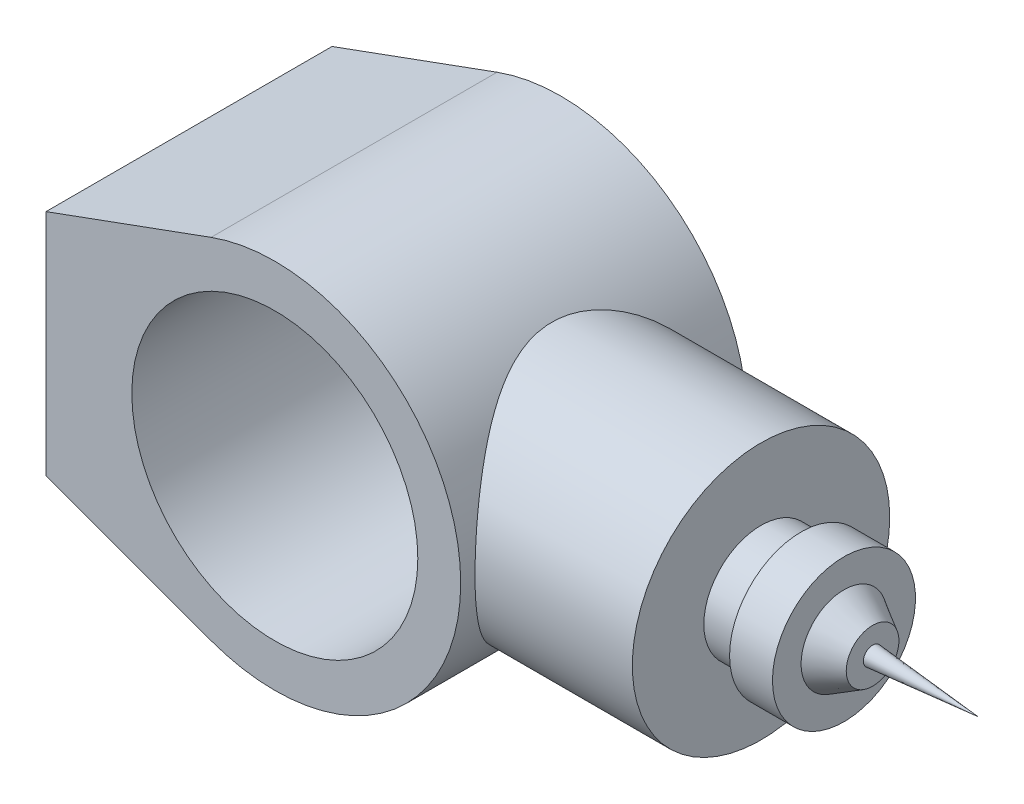
SolidWorks part; units mm, degrees
ref_plane "Alzado" through (0, 0, 0) normal (0, 0, 1) x (1, 0, 0)
ref_plane "Planta" through (0, 0, 0) normal (0, 1, 0) x (1, 0, 0)
ref_plane "Vista lateral" through (0, 0, 0) normal (1, 0, 0) x (0, 0, -1)
sketch "Croquis1" plane through (0, 0, 0) normal (0, 0, 1) x (1, 0, 0)
  line L0 (-80, -40) -> (-80, 40)
  line L1 (-80, -40) -> (-22.2817, -61.0617)
  line L2 (-80, 40) -> (-22.2817, 61.0617)
  arc A0 (-22.2817, -61.0617) -> (-22.2817, 61.0617) centre (0, 0) ccw
  circle A1 centre (0, 0) radius 50
  point P7 (-80, 0)
  dimension "D1" = 130
  dimension "D2" = 100
  dimension "D3" = 80
  dimension "D4" = 80
extrude "Saliente-Extruir1" add sketch "Croquis1" along normal mid plane 100
ref_plane "Plano1" through (120, 0, 0) normal (1, 0, 0) x (0, 0, -1)
sketch "Croquis2" plane through (120, 0, 0) normal (1, 0, 0) x (0, 0, -1)
  circle A0 centre (0, 0) radius 45
  dimension "D1" = 90
extrude "Saliente-Extruir2" add sketch "Croquis2" against normal up to next
sketch "Croquis3" plane through (0, 0, 0) normal (0, 0, 1) x (1, 0, 0)
  line L0 (0, 0) -> (267.2394, 0) construction
  line L1 (120, 0) -> (120, -20)
  line L2 (120, -45) -> (120, 45) construction
  line L3 (120, -20) -> (134, -20)
  line L4 (134, -20) -> (134, -25)
  line L5 (134, -25) -> (149, -25)
  line L6 (149, -25) -> (149, -15)
  line L7 (149, -15) -> (159, -9.2153)
  line L8 (159, -9.2153) -> (159, -3.2153)
  line L9 (120, 0) -> (195.86, 0)
  line L10 (159, -3.2153) -> (195.86, 0)
  dimension "D1" = 20
  dimension "D2" = 14
  dimension "D3" = 5
  dimension "D4" = 15
  dimension "D5" = 10
  dimension "D6" = 10
  dimension "D7" = 37
  dimension "D8" = 6
revolve "Revolución1" add sketch "Croquis3" angle 360 about L0
